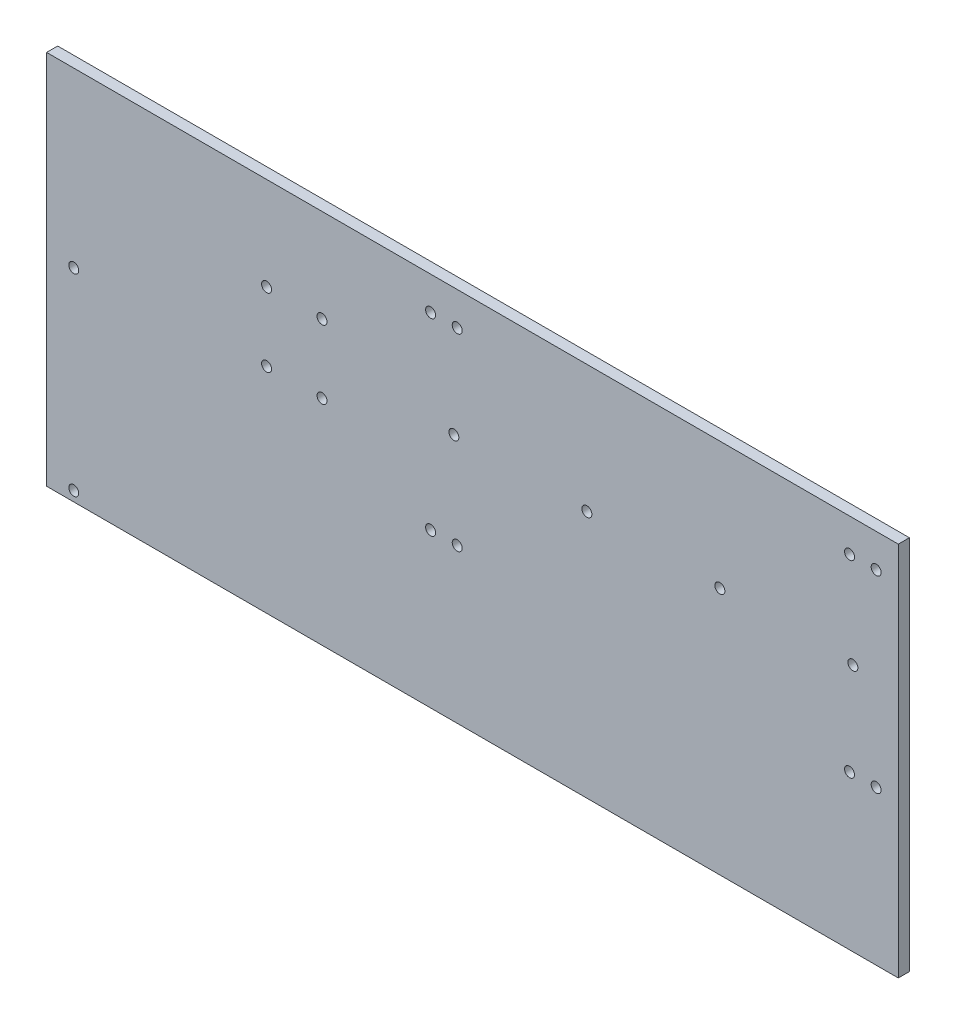
SolidWorks part; units mm, degrees
ref_plane "Front Plane" through (0, 0, 0) normal (0, 0, 1) x (1, 0, 0)
ref_plane "Top Plane" through (0, 0, 0) normal (0, 1, 0) x (1, 0, 0)
ref_plane "Right Plane" through (0, 0, 0) normal (1, 0, 0) x (0, 0, -1)
sketch "Sketch1" plane through (0, 0, 0) normal (0, 0, 1) x (1, 0, 0)
  line L1 (-192.1189, -84.7584) -> (192.1189, -84.7584)
  line L2 (-192.1189, -84.7584) -> (-192.1189, 84.7584)
  line L3 (-192.1189, 84.7584) -> (192.1189, 84.7584)
  line L4 (192.1189, -84.7584) -> (192.1189, 84.7584)
  line L5 (-192.1189, -84.7584) -> (192.1189, 84.7584) construction
  line L6 (-192.1189, 84.7584) -> (192.1189, -84.7584) construction
  point P0 (-67.8811, 42.7584)
  point P5 (-179.8689, -80.2584)
  point P6 (182.1189, 69.7584)
  point P7 (170.1189, 69.7584)
  point P8 (171.6189, 27.2584)
  point P9 (182.1189, -15.2416)
  point P10 (170.1189, -15.2416)
  point P11 (-6.8811, 69.7584)
  point P12 (-18.8811, 69.7584)
  point P13 (-6.8811, -15.2416)
  point P14 (-18.8811, -15.2416)
  point P15 (-92.8811, 42.7584)
  point P16 (111.6189, 27.2584)
  point P17 (51.6189, 27.2584)
  point P18 (-8.3811, 27.2584)
  point P19 (-92.8811, 11.7584)
  point P20 (-67.8811, 11.7584)
  point P21 (-179.8689, 6.7416)
  dimension "D1" = 15
  dimension "D2" = 15
  dimension "D3" = 12
  dimension "D4" = 10
  dimension "D5" = 85
  dimension "D6" = 10
  dimension "D8" = 42.5
  dimension "D9" = 1.5
  dimension "D11" = 27
  dimension "D12" = 49
  dimension "D13" = 27
  dimension "D14" = 49
  dimension "D15" = 25
  dimension "D16" = 25
  dimension "D17" = 31
  dimension "D18" = 31
  dimension "D7" = 2
  dimension "D10" = 4
extrude "Boss-Extrude1" add sketch "Sketch1" along normal blind 5
hole_wizard "M4 Clearance Hole1" positions "Sketch6" profile "Sketch7" hole size "M4" standard "ISO" end condition through all
sketch "Sketch6" plane through (0, 0, 0) normal (0, 0, -1) x (-1, 0, 0)
  point P0 (92.8811, 42.7584)
  point P3 (92.8811, 11.7584)
  point P6 (67.8811, 11.7584)
  point P9 (67.8811, 42.7584)
  point P12 (18.8811, 69.7584)
  point P15 (6.8811, 69.7584)
  point P18 (8.3811, 27.2584)
  point P21 (18.8811, -15.2416)
  point P24 (6.8811, -15.2416)
  point P27 (-51.6189, 27.2584)
  point P30 (-111.6189, 27.2584)
  point P33 (-171.6189, 27.2584)
  point P36 (-170.1189, -15.2416)
  point P39 (-182.1189, -15.2416)
  point P42 (-170.1189, 69.7584)
  point P45 (-182.1189, 69.7584)
sketch "Sketch7" plane through (-92.8811, 42.7584, 0) normal (1, 0, 0) x (0, 1, 0)
  line L0 (0, 0) -> (0, 5)
  line L1 (0, 5) -> (2.25, 5)
  line L2 (2.25, 5) -> (2.25, 0)
  line L5 (2.25, 0) -> (0, 0)
  line L11 (0, -6.35) -> (0, 107.95) construction
  dimension "Thru Hole Dia." = 4.5
  dimension "Thru Hole Depth" = 5
hole_wizard "M4 Clearance Hole2" positions "Sketch8" profile "Sketch9" hole size "M4" standard "ISO" end condition through all
sketch "Sketch8" plane through (0, 0, 0) normal (0, 0, -1) x (-1, 0, 0)
  point P0 (179.8689, 6.7416)
  point P3 (179.8689, -80.2584)
sketch "Sketch9" plane through (-179.8689, 6.7416, 0) normal (1, 0, 0) x (0, 1, 0)
  line L0 (0, 0) -> (0, 5)
  line L1 (0, 5) -> (2.25, 5)
  line L2 (2.25, 5) -> (2.25, 0)
  line L5 (2.25, 0) -> (0, 0)
  line L11 (0, -6.35) -> (0, 107.95) construction
  dimension "Thru Hole Dia." = 4.5
  dimension "Thru Hole Depth" = 5
